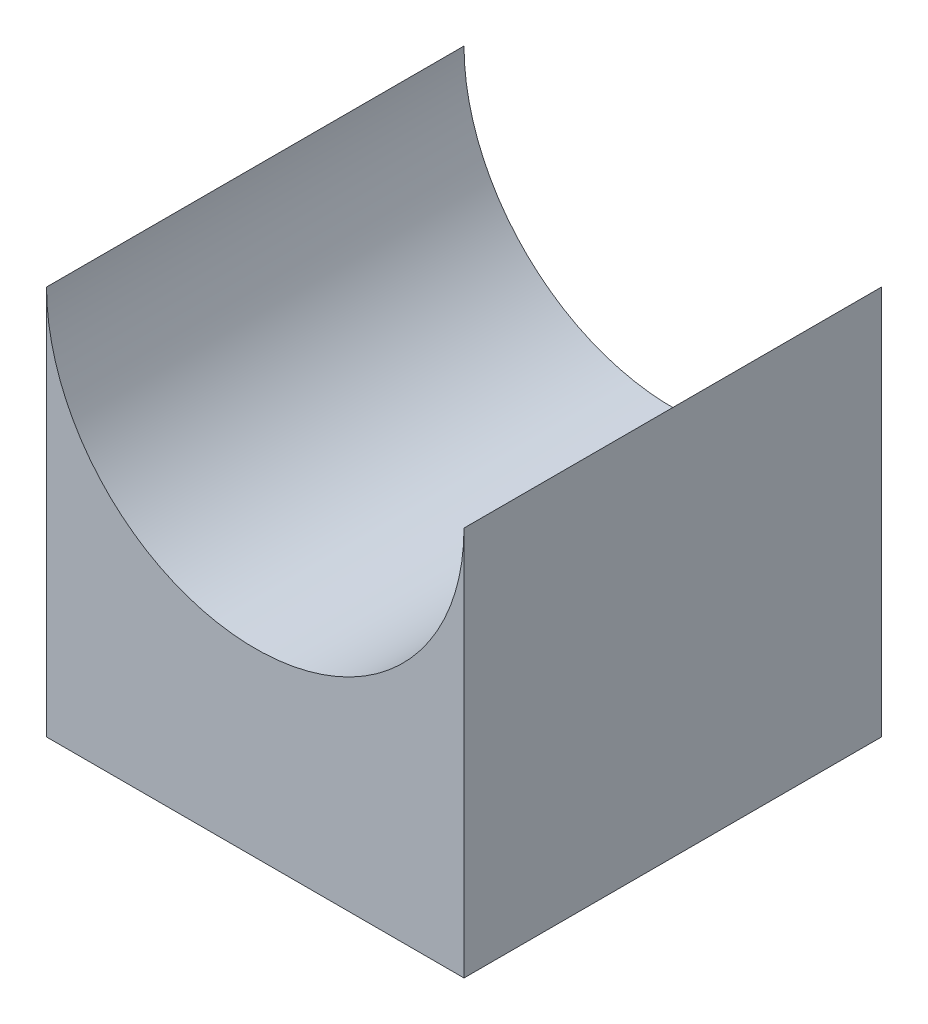
SolidWorks part; units mm, degrees
ref_plane "정면" through (0, 0, 0) normal (0, 0, 1) x (1, 0, 0)
ref_plane "윗면" through (0, 0, 0) normal (0, 1, 0) x (1, 0, 0)
ref_plane "우측면" through (0, 0, 0) normal (1, 0, 0) x (0, 0, -1)
sketch "스케치1" plane through (0, 0, 0) normal (0, 0, 1) x (1, 0, 0)
  line L0 (0, 0) -> (3, 0)
  line L1 (3, 0) -> (3, 2.8)
  line L2 (0, 0) -> (0, 2.8)
  arc A0 (0, 2.8) -> (3, 2.8) centre (1.5, 2.8) ccw
  point P7 (0, 0)
  point P8 (3, 3.9144)
  dimension "D1" = 1.5
  dimension "D2" = 2.8
extrude "보스-돌출1" add sketch "스케치1" along normal blind 3 contours L0 L1 A0 L2
